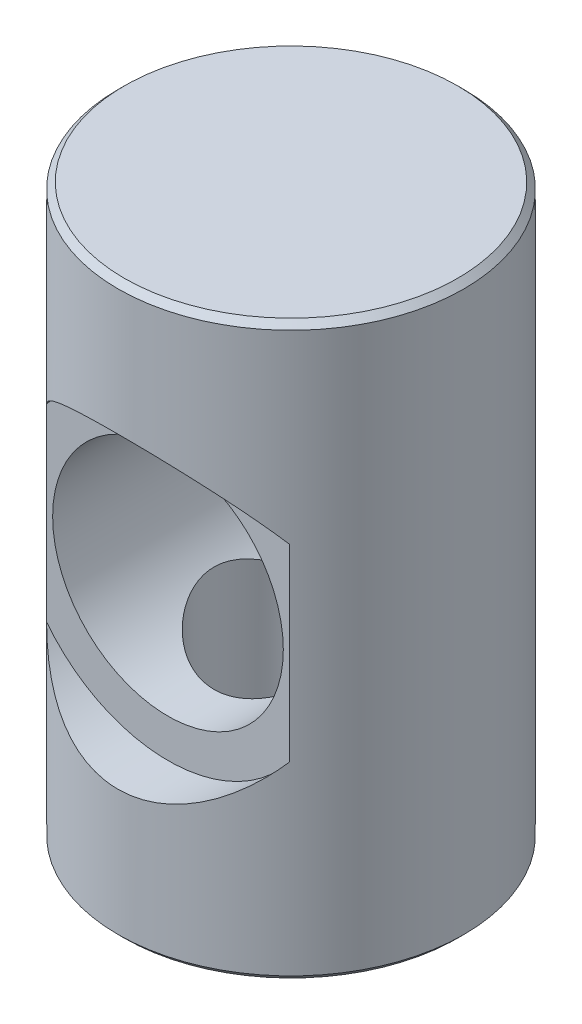
SolidWorks part; units mm, degrees
material "Free-Cutting Brass, UNS C36000"
ref_plane "Front Plane" through (0, 0, 0) normal (0, 0, 1) x (1, 0, 0)
ref_plane "Top Plane" through (0, 0, 0) normal (0, 1, 0) x (1, 0, 0)
ref_plane "Right Plane" through (0, 0, 0) normal (1, 0, 0) x (0, 0, -1)
sketch "Sketch1" plane through (0, 0, 0) normal (0, 1, 0) x (1, 0, 0)
  circle A0 centre (0, 0) radius 7.1374
  dimension "D1" = 14.2748
extrude "Boss-Extrude1" add sketch "Sketch1" along normal blind 23.5966
chamfer "Chamfer1" distance 0.254 angle 45 1 edges at (0, 0, 7.1374)
chamfer "Chamfer2" distance 0.254 angle 45 1 edges at (0, 23.5966, 7.1374)
sketch "Sketch2" plane through (0, 0, 0) normal (0, 0, 1) x (1, 0, 0)
  line L0 (0, 0) -> (0, 23.5966) construction
  line L1 (6.8834, 23.5966) -> (-6.8834, 23.5966) construction
  circle A1 centre (0, 11.7983) radius 4.7625
  dimension "D1" = 9.525
extrude "Cut-Extrude1" cut sketch "Sketch2" against normal mid plane 14.351 contours A1
ref_plane "Plane1" through (0, 0, 5.08) normal (0, 0, 1) x (1, 0, 0)
sketch "Sketch3" plane through (0, 0, 5.08) normal (0, 0, 1) x (1, 0, 0)
  circle A0 centre (0, 11.7983) radius 6.35
  dimension "D1" = 12.7
extrude "Cut-Extrude2" cut sketch "Sketch3" along normal through all
mirror "Mirror1" about plane through (0, 0, 0) normal (0, 0, 1) of "Cut-Extrude2"
sketch "Sketch4" plane through (0, 0, 0) normal (0, -1, 0) x (1, 0, 0)
  circle A0 centre (0, 0) radius 3.175
  dimension "D1" = 6.35
extrude "Cut-Extrude3" cut sketch "Sketch4" against normal up to next
